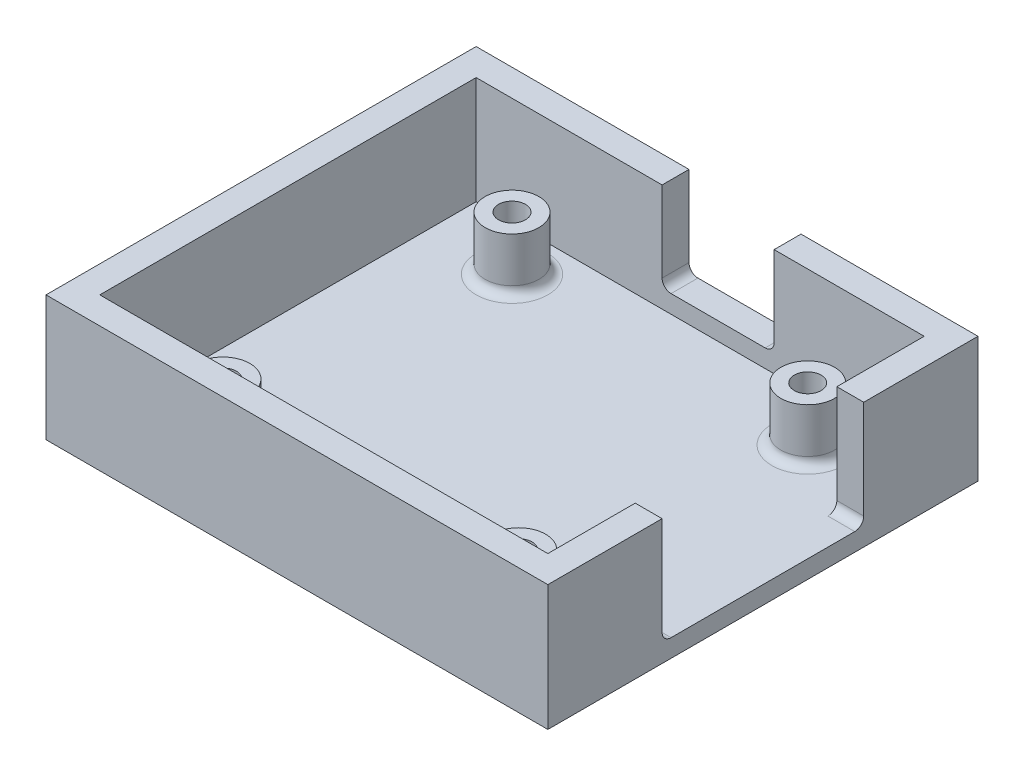
SolidWorks part; units mm, degrees
ref_plane "Front Plane" through (0, 0, 0) normal (0, 0, 1) x (1, 0, 0)
ref_plane "Top Plane" through (0, 0, 0) normal (0, 1, 0) x (1, 0, 0)
ref_plane "Right Plane" through (0, 0, 0) normal (1, 0, 0) x (0, 0, -1)
sketch "Sketch1" plane through (0, 0, 0) normal (0, 1, 0) x (1, 0, 0)
  line L1 (-20.0704, 23.4925) -> (35.9296, 23.4925)
  line L2 (-20.0704, 23.4925) -> (-20.0704, -24.5075)
  line L3 (-20.0704, -24.5075) -> (35.9296, -24.5075)
  line L4 (35.9296, 23.4925) -> (35.9296, -24.5075)
  dimension "D1" = 48
  dimension "D2" = 56
extrude "Boss-Extrude1" add sketch "Sketch1" along normal blind 14
sketch "Sketch3" plane through (0, 14, 0) normal (0, 1, 0) x (1, 0, 0)
  line L0 (-17.0704, 20.4925) -> (32.9296, 20.4925)
  line L1 (-17.0704, 20.4925) -> (-17.0704, -21.5075)
  line L2 (-17.0704, -21.5075) -> (32.9296, -21.5075)
  line L3 (32.9296, 20.4925) -> (32.9296, -21.5075)
  line L4 (35.9296, -24.5075) -> (35.9296, 23.4925) construction
  line L5 (-20.0704, -24.5075) -> (35.9296, -24.5075) construction
  dimension "D1" = 42
  dimension "D2" = 50
  dimension "D3" = 3
  dimension "D4" = 3
extrude "Cut-Extrude1" cut sketch "Sketch3" against normal blind 12
sketch "Sketch4" plane through (0, 2, 0) normal (0, 1, 0) x (1, 0, 0)
  line L0 (-17.0704, -21.5075) -> (32.9296, -21.5075) construction
  line L3 (32.9296, 20.4925) -> (-17.0704, 20.4925) construction
  line L4 (-17.0704, 20.4925) -> (-17.0704, -21.5075) construction
  line L8 (-17.0704, -21.5075) -> (32.9296, -21.5075) construction
  line L9 (32.9296, -21.5075) -> (32.9296, 20.4925) construction
  circle A0 centre (-8.0704, 15.4925) radius 3
  circle A1 centre (24.9296, 15.4925) radius 3
  circle A2 centre (24.9296, -16.7575) radius 3
  circle A3 centre (-8.0704, -16.7575) radius 3
  circle A4 centre (-8.0704, 15.4925) radius 1.5
  circle A5 centre (24.9296, 15.4925) radius 1.5
  circle A6 centre (-8.0704, -16.7575) radius 1.5
  circle A7 centre (24.9296, -16.7575) radius 1.5
  dimension "D1" = 5
  dimension "D8" = 8
  dimension "D2" = 9
  dimension "D3" = 4.75
  dimension "D4" = 33
  dimension "D5" = 9
  dimension "D6" = 5
  dimension "D7" = 33
  dimension "D9" = 32.25
  dimension "D10" = 4.75
extrude "Boss-Extrude2" add sketch "Sketch4" along normal blind 6
sketch "Sketch5" plane through (32.9296, 0, 0) normal (-1, 0, 0) x (0, 0, 1)
  line L0 (-20.4925, 2) -> (-20.4925, 14) construction
  line L1 (-10.7425, 14) -> (11.7575, 14)
  line L2 (-10.7425, 14) -> (-10.7425, 2)
  line L3 (-10.7425, 2) -> (11.7575, 2)
  line L4 (11.7575, 14) -> (11.7575, 2)
  line L9 (21.5075, 14) -> (-20.4925, 14) construction
  dimension "D1" = 9.75
  dimension "D2" = 22.5
  dimension "D4" = 12
extrude "Cut-Extrude2" cut sketch "Sketch5" against normal up to surface (3 mm away) up to face at (35.9296, 7, 0.5075)
sketch "Sketch6" plane through (0, 0, -20.4925) normal (0, 0, 1) x (1, 0, 0)
  line L0 (32.9296, 14) -> (-17.0704, 14) construction
  line L1 (3.6796, 14) -> (16.1796, 14)
  line L2 (3.6796, 14) -> (3.6796, 4)
  line L3 (3.6796, 4) -> (16.1796, 4)
  line L4 (16.1796, 14) -> (16.1796, 4)
  line L5 (-17.0704, 2) -> (-17.0704, 14) construction
  line L7 (32.9296, 2) -> (32.9296, 14) construction
  dimension "D1" = 12.5
  dimension "D2" = 10
  dimension "D3" = 20.75
  dimension "D4" = 16.75
extrude "Cut-Extrude3" cut sketch "Sketch6" against normal up to surface (3 mm away) up to face at (7.9296, 7, -23.4925)
fillet "Fillet1" radius 1 4 edges at (16.1796, 4, -21.9925) (3.6796, 4, -21.9925) (34.4296, 2, -10.7425) (34.4296, 2, 11.7575)
fillet "Fillet2" radius 1 4 edges at (-8.0704, 2, -12.4925) (24.9296, 2, -12.4925) (-8.0704, 2, 19.7575) (24.9296, 2, 19.7575)
